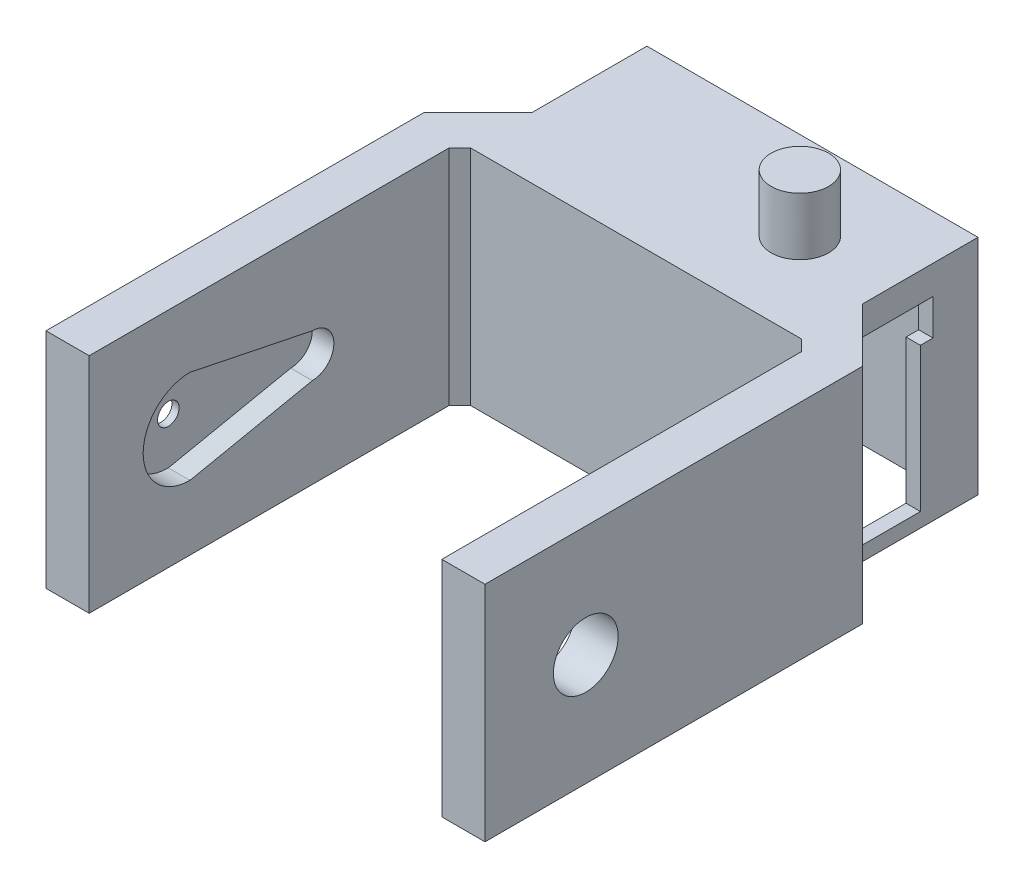
SolidWorks part; units mm, degrees
material "ABS"
ref_plane "Front Plane" through (0, 0, 0) normal (0, 0, 1) x (1, 0, 0)
ref_plane "Top Plane" through (0, 0, 0) normal (0, 1, 0) x (1, 0, 0)
ref_plane "Right Plane" through (0, 0, 0) normal (1, 0, 0) x (0, 0, -1)
sketch "Sketch1" plane through (0, 0, 0) normal (0, 1, 0) x (1, 0, 0)
  line L1 (-23, -12.25) -> (23, -12.25)
  line L2 (-23, -12.25) -> (-23, 12.25)
  line L3 (-23, 12.25) -> (23, 12.25)
  line L4 (23, -12.25) -> (23, 12.25)
  line L5 (-23, -12.25) -> (23, 12.25) construction
  line L6 (-23, 12.25) -> (23, -12.25) construction
  point P0 (0, 0)
  dimension "D1" = 24.5
  dimension "D2" = 46
extrude "Body" add sketch "Sketch1" along normal blind 31
sketch "Sketch3" plane through (0, 0, 0) normal (0, 1, 0) x (1, 0, 0)
  line L0 (-23, -12.25) -> (23, -12.25) construction
  line L1 (-21, 10.25) -> (21, 10.25)
  line L2 (-21, 10.25) -> (-21, -10.25)
  line L3 (-21, -10.25) -> (21, -10.25)
  line L4 (21, 10.25) -> (21, -10.25)
  line L5 (-21, 10.25) -> (21, -10.25) construction
  line L6 (-21, -10.25) -> (21, 10.25) construction
  line L7 (23, -12.25) -> (23, 12.25) construction
  point P0 (0, 0)
  dimension "D1" = 2
  dimension "D2" = 2
extrude "Servo Hole" cut sketch "Sketch3" along normal blind 29
sketch "Sketch6" plane through (0, 31, 0) normal (0, 1, 0) x (1, 0, 0)
  line L0 (23, -12.25) -> (23, 12.25) construction
  line L2 (10.5, 0) -> (0, 0) construction
  circle A0 centre (10.5, 0) radius 4
  dimension "D2" = 8
  dimension "D1" = 12.5
extrude "Boss-Extrude3" add sketch "Sketch6" along normal blind 8
sketch "Sketch8" plane through (0, 0, 0) normal (0, -1, 0) x (1, 0, 0)
  line L0 (-23, 12.25) -> (-24.5, 13.75)
  line L1 (-23, 3.7647) -> (-30.5, 11.2647)
  line L2 (-23, -12.25) -> (-23, 12.25) construction
  line L3 (-30.5, 11.2647) -> (-30.5, 63.75)
  line L4 (-30.5, 63.75) -> (-24.5, 63.75)
  line L5 (-24.5, 63.75) -> (-24.5, 13.75)
  line L6 (0, 0) -> (0, 31.6845) construction
  line L7 (24.5, 63.75) -> (24.5, 13.75)
  line L8 (30.5, 63.75) -> (24.5, 63.75)
  line L9 (30.5, 11.2647) -> (30.5, 63.75)
  line L10 (23, 3.7647) -> (30.5, 11.2647)
  line L11 (23, 12.25) -> (24.5, 13.75)
  line L12 (-23, 12.25) -> (-23, 3.7647)
  line L13 (23, 12.25) -> (23, 3.7647)
  dimension "D1" = 1.5
  dimension "D2" = 1.5
  dimension "D3" = 6
  dimension "D4" = 6
  dimension "D5" = 50
  dimension "D6" = 49
extrude "Boss-Extrude4" add sketch "Sketch8" against normal up to surface (31 mm away) up to face at (10.5, 31, -4)
sketch "Sketch5" plane through (23, 0, 0) normal (-1, 0, 0) x (0, 0, 1)
  line L8 (-6, 27) -> (6, 27)
  line L13 (6, 27) -> (6, 22)
  line L14 (6, 22) -> (4.25, 22)
  line L17 (4.25, 22) -> (4.25, 2)
  line L18 (4.25, 2) -> (-4.25, 2)
  line L19 (3.7647, 0) -> (-12.25, 0) construction
  line L21 (-4.25, 2) -> (-4.25, 22)
  line L22 (-4.25, 22) -> (-6, 22)
  line L23 (-6, 22) -> (-6, 27)
  line L25 (-12.25, 31) -> (3.7647, 31) construction
  dimension "D1" = 4
  dimension "D2" = 2
  dimension "D3" = 5
  dimension "D4" = 12
  dimension "D5" = 5
  dimension "D6" = 1.75
  dimension "D7" = 1.75
  dimension "D8" = 4.25
extrude "Cut-Extrude3" cut sketch "Sketch5" against normal blind 29 and the other way blind 2
sketch "Sketch10" plane through (-24.5, 0, 0) normal (1, 0, 0) x (0, 0, -1)
  line L0 (-63.75, 31) -> (-63.75, 0) construction
  line L3 (-32.75, 12.5) -> (-49.75, 9)
  line L5 (-49.75, 22) -> (-32.75, 18.5)
  line L6 (-63.75, 31) -> (-13.75, 31) construction
  arc A1 (-49.75, 22) -> (-49.75, 9) centre (-49.75, 15.5) ccw
  arc A3 (-32.75, 18.5) -> (-32.75, 12.5) centre (-32.75, 15.5) cw
  dimension "D2" = 15.5
  dimension "D1" = 14
  dimension "D3" = 17
  dimension "D4" = 6.5
  dimension "D5" = 3
extrude "Cut-Extrude4" cut sketch "Sketch10" against normal blind 3
sketch "Sketch11" plane through (-24.5, 0, 0) normal (1, 0, 0) x (0, 0, -1)
  circle A0 centre (-49.75, 15.5) radius 1.5
  dimension "D1" = 3
extrude "Cut-Extrude5" cut sketch "Sketch11" against normal through all both and the other way through all
sketch "Sketch12" plane through (30.5, 0, 0) normal (1, 0, 0) x (0, 0, -1)
  circle A0 centre (-49.75, 15.5) radius 4.5
  dimension "D1" = 9
extrude "Cut-Extrude6" cut sketch "Sketch12" against normal blind 6
sketch "Sketch13" plane through (-30.5, 0, 0) normal (-1, 0, 0) x (0, 0, 1)
  circle A0 centre (49.75, 15.5) radius 5
  dimension "D1" = 10
extrude "Cut-Extrude7" cut sketch "Sketch13" against normal blind 2 contours A0
